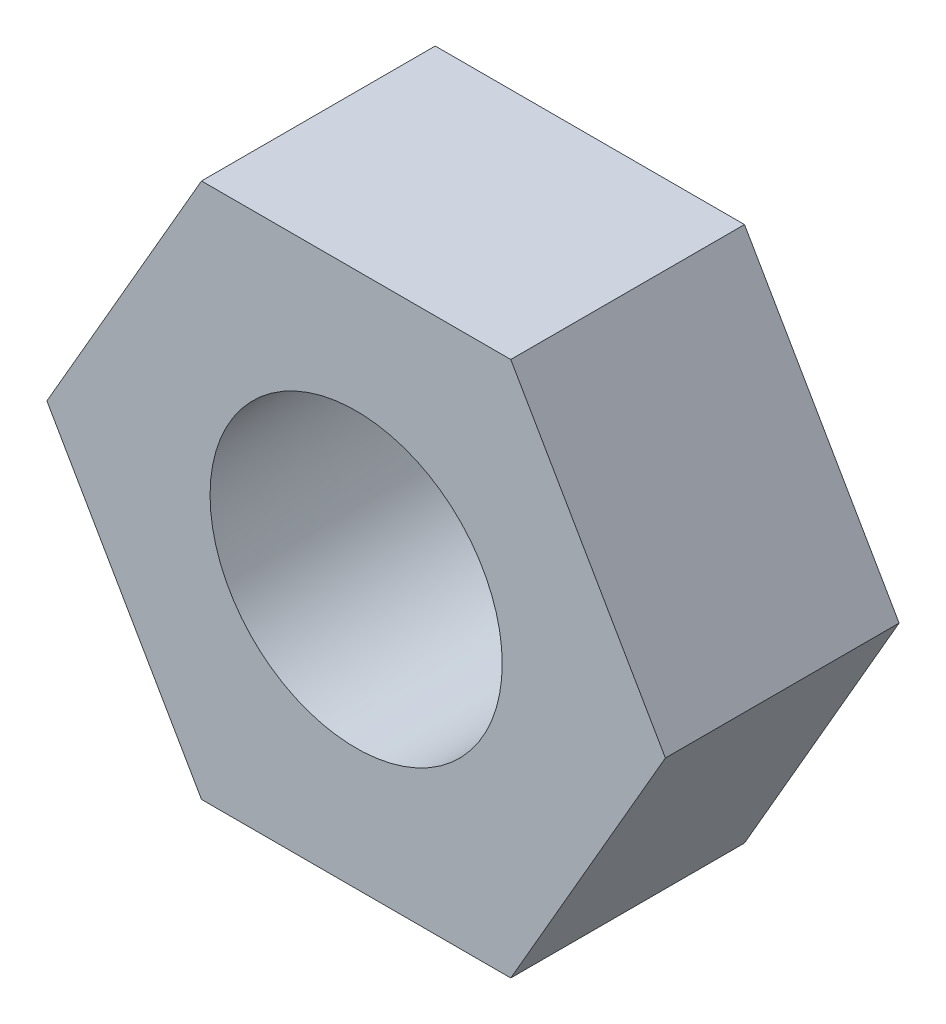
SolidWorks part; units mm, degrees
ref_plane "Front Plane" through (0, 0, 0) normal (0, 0, 1) x (1, 0, 0)
ref_plane "Top Plane" through (0, 0, 0) normal (0, 1, 0) x (1, 0, 0)
ref_plane "Right Plane" through (0, 0, 0) normal (1, 0, 0) x (0, 0, -1)
sketch "Sketch1" plane through (0, 0, 0) normal (0, 0, 1) x (1, 0, 0)
  line L1 (3.1754, 0) -> (1.5877, 2.75)
  line L2 (1.5877, 2.75) -> (-1.5877, 2.75)
  line L3 (-1.5877, 2.75) -> (-3.1754, 0)
  line L4 (-3.1754, 0) -> (-1.5877, -2.75)
  line L5 (-1.5877, -2.75) -> (1.5877, -2.75)
  line L6 (1.5877, -2.75) -> (3.1754, 0)
  circle A0 centre (0, 0) radius 2.75 construction
extrude "Boss-Extrude1" add sketch "Sketch1" along normal blind 2.4
sketch "Sketch2" plane through (0, 0, 2.4) normal (0, 0, 1) x (1, 0, 0)
  circle A0 centre (0, 0) radius 1.5
  dimension "D1" = 3
extrude "Cut-Extrude1" cut sketch "Sketch2" against normal blind 2.4
